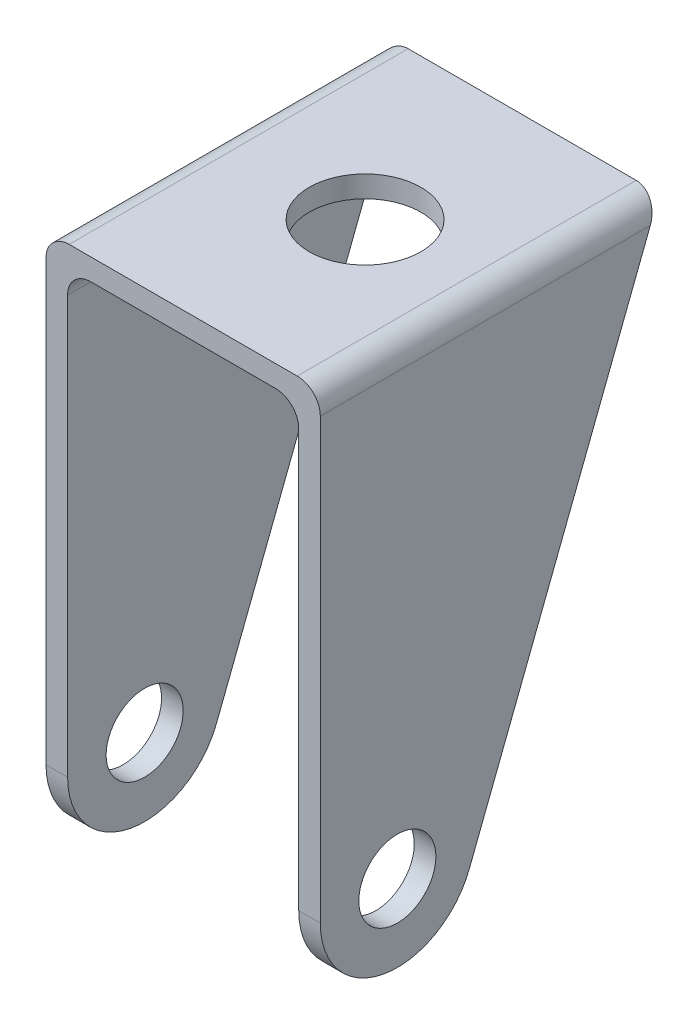
SolidWorks part; units mm, degrees
material "Galvanized Steel"
ref_plane "Front Plane" through (0, 0, 0) normal (0, 0, 1) x (1, 0, 0)
ref_plane "Top Plane" through (0, 0, 0) normal (0, 1, 0) x (1, 0, 0)
ref_plane "Right Plane" through (0, 0, 0) normal (1, 0, 0) x (0, 0, -1)
sketch "Sketch1" plane through (0, 0, 0) normal (0, 0, 1) x (1, 0, 0)
  line L0 (0, 0) -> (0, 70)
  line L1 (0, 70) -> (30, 70)
  line L2 (30, 70) -> (30, 0)
  dimension "D1" = 70
  dimension "D2" = 30
extrude "Extrude-Thin1" add sketch "Sketch1" along normal blind 44 thin thin type one direction reverse wall 2.8
sketch "Sketch3" plane through (32.8, 0, 0) normal (1, 0, 0) x (0, 0, -1)
  line L0 (-44, 12.8) -> (-44, 72.8)
  line L1 (-24.6768, 9.1835) -> (0, 72.8)
  line L4 (0, 0) -> (0, 72.8)
  line L5 (0, 72.8) -> (-44, 72.8)
  line L6 (-44, 72.8) -> (-44, 0)
  line L7 (-44, 0) -> (0, 0)
  line L9 (0, 72.8) -> (-44, 72.8)
  arc A1 (-24.6768, 9.1835) -> (-44, 12.8) centre (-34, 12.8) cw
  dimension "D3" = 60
  dimension "D2" = 10
  dimension "D1" = 0
extrude "Cut-Extrude1" cut sketch "Sketch3" against normal through all flip side to cut
sketch "Sketch4" plane through (-2.8, 0, 0) normal (-1, 0, 0) x (0, 0, 1)
  line L0 (44, 12.8) -> (44, 72.8) construction
  line L1 (44, 72.8) -> (0, 72.8) construction
  circle A0 centre (34, 12.8) radius 5
  dimension "D1" = 10
  dimension "D2" = 10
  dimension "D3" = 60
extrude "Cut-Extrude2" cut sketch "Sketch4" against normal through all
sketch "Sketch5" plane through (0, 72.8, 0) normal (0, 1, 0) x (1, 0, 0)
  line L0 (32.8, -44) -> (32.8, 0) construction
  line L2 (-2.8, -44) -> (32.8, -44) construction
  circle A0 centre (16.61, -22) radius 7.25
  dimension "D1" = 14.5
  dimension "D2" = 16.19
  dimension "D3" = 22
extrude "Cut-Extrude3" cut sketch "Sketch5" against normal blind 10
fillet "Fillet3" radius 3 4 edges at (0, 70, 22.5431) (30, 70, 22.5431) (-2.8, 72.8, 22) (32.8, 72.8, 22)
